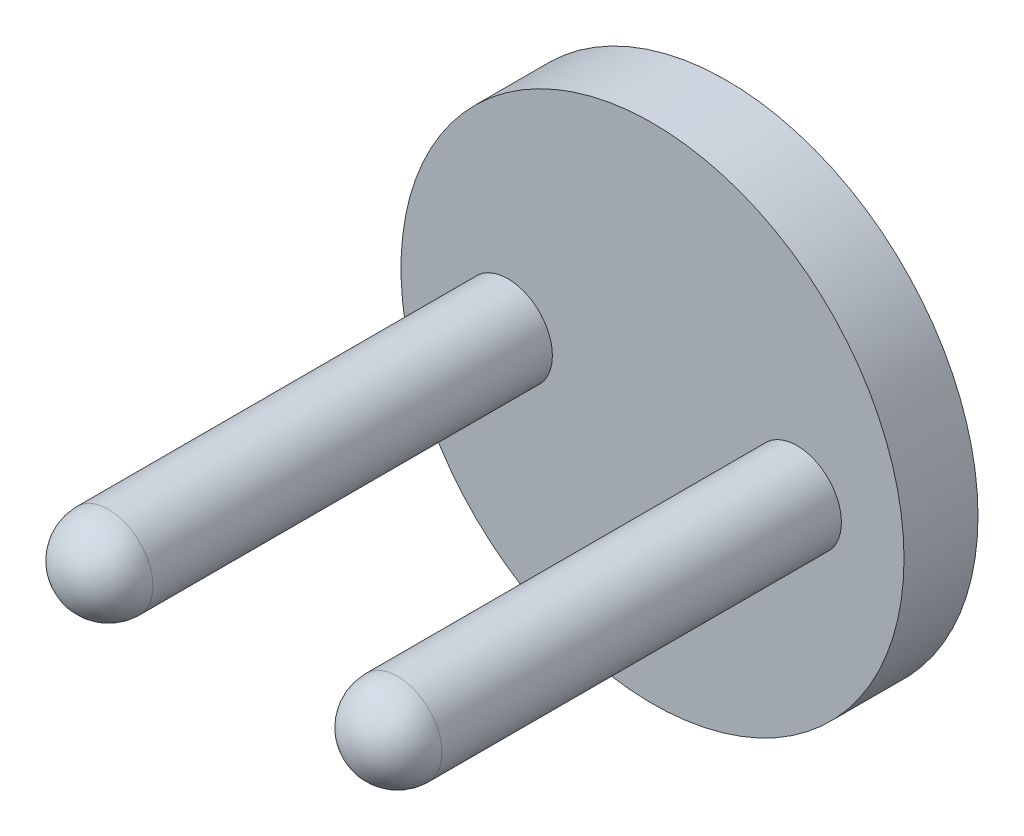
SolidWorks part; units mm, degrees
material "1060 Alloy"
ref_plane "Front Plane" through (0, 0, 0) normal (0, 0, 1) x (1, 0, 0)
ref_plane "Top Plane" through (0, 0, 0) normal (0, 1, 0) x (1, 0, 0)
ref_plane "Right Plane" through (0, 0, 0) normal (1, 0, 0) x (0, 0, -1)
sketch "Sketch1" plane through (0, 0, 0) normal (0, 0, 1) x (1, 0, 0)
  circle A0 centre (0, 0) radius 17
  dimension "D1" = 34
extrude "Boss-Extrude1" add sketch "Sketch1" along normal blind 5
sketch "Sketch2" plane through (0, 0, 5) normal (0, 0, 1) x (1, 0, 0)
  line L0 (0, 0) -> (9.7682, 0) construction
  line L1 (0, 0) -> (-9.7682, 0) construction
  circle A0 centre (-9.7682, 0) radius 3
  circle A1 centre (9.7682, 0) radius 3
  point P6 (-9.7682, 0)
  dimension "D1" = 6
extrude "Boss-Extrude2" add sketch "Sketch2" along normal blind 30
sketch "Sketch3" plane through (0, 0, 0) normal (0, 0, -1) x (-1, 0, 0)
  circle A0 centre (0, 0) radius 3.125
  dimension "D1" = 6.25
extrude "Boss-Extrude3" add sketch "Sketch3" along normal blind 4
fillet "Fillet1" radius 3 2 edges at (12.7682, 0, 35) (-6.7682, 0, 35)
